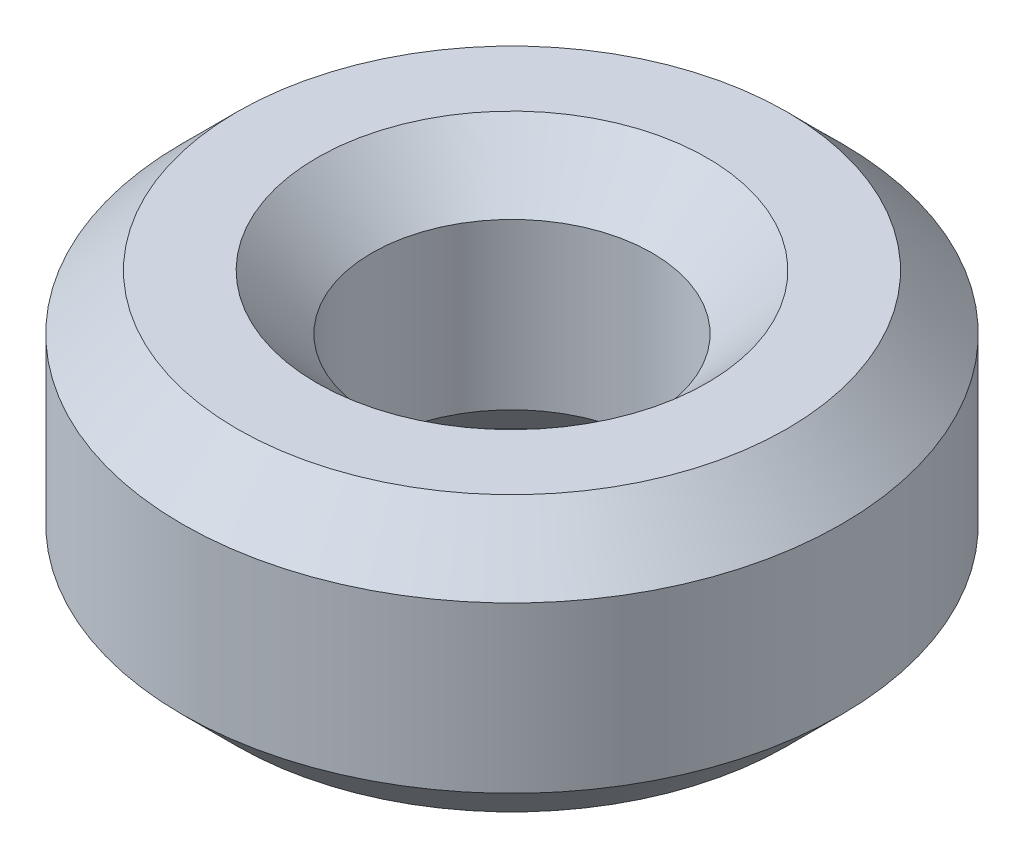
SolidWorks part; units mm, degrees
ref_plane "Front Plane" through (0, 0, 0) normal (0, 0, 1) x (1, 0, 0)
ref_plane "Top Plane" through (0, 0, 0) normal (0, 1, 0) x (1, 0, 0)
ref_plane "Right Plane" through (0, 0, 0) normal (1, 0, 0) x (0, 0, -1)
sketch "Sketch1" plane through (0, 0, 0) normal (0, 1, 0) x (1, 0, 0)
  circle A0 centre (0, 0) radius 6
  circle A1 centre (0, 0) radius 2.55
  dimension "D1" = 5.1
  dimension "D2" = 12
extrude "Boss-Extrude1" add sketch "Sketch1" along normal blind 5 contours A0 A1
chamfer "Chamfer1" distance 1 angle 45 4 edges at (0, 0, 6) (0, 0, 2.55) (0, 5, 6) (0, 5, 2.55)
